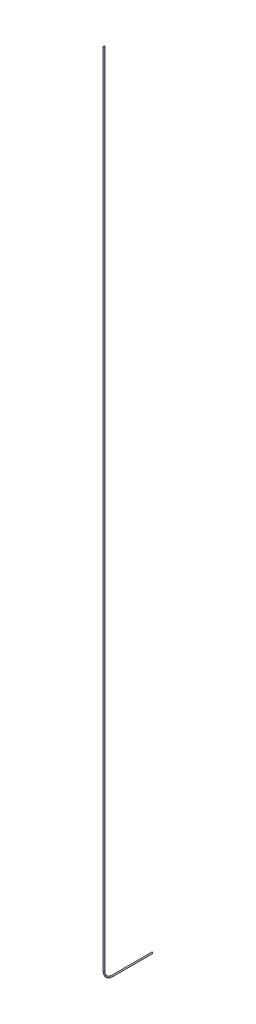
SolidWorks part; units mm, degrees
ref_plane "正面" through (0, 0, 0) normal (0, 0, 1) x (1, 0, 0)
ref_plane "平面" through (0, 0, 0) normal (0, 1, 0) x (1, 0, 0)
ref_plane "右側面" through (0, 0, 0) normal (1, 0, 0) x (0, 0, -1)
sketch "ｽｹｯﾁ1" plane through (0, 0, 0) normal (0, 0, 1) x (1, 0, 0)
  circle A0 centre (0, 0) radius 0.4
  dimension "D1" = 0.8
extrude "ﾎﾞｽ - 押し出し1" add sketch "ｽｹｯﾁ1" along normal blind 20
sketch "ｽｹｯﾁ2" plane through (0, 0, 20) normal (0, 0, 1) x (1, 0, 0)
  circle A1 centre (0, 0) radius 0.4
  circle A2 centre (0, 0) radius 0.4
  dimension "D1" = 0
sketch "ｽｹｯﾁ3" plane through (0, 0, 0) normal (1, 0, 0) x (0, 0, -1)
  line L0 (-20, 0) -> (-25, 0)
  line L1 (-20, 0.4) -> (-20, -0.4) construction
  line L2 (-30, 5) -> (-30, 505)
  line L3 (-20, 0.4) -> (-20, -0.4) construction
  arc A0 (-25, 0) -> (-30, 5) centre (-25, 5) cw
  point P8 (-30, 0)
  dimension "D2" = 5
  dimension "D1" = 10
  dimension "D3" = 500
sweep "ｽｲｰﾌﾟ1" add profiles "ｽｹｯﾁ2" path "ｽｹｯﾁ3"
